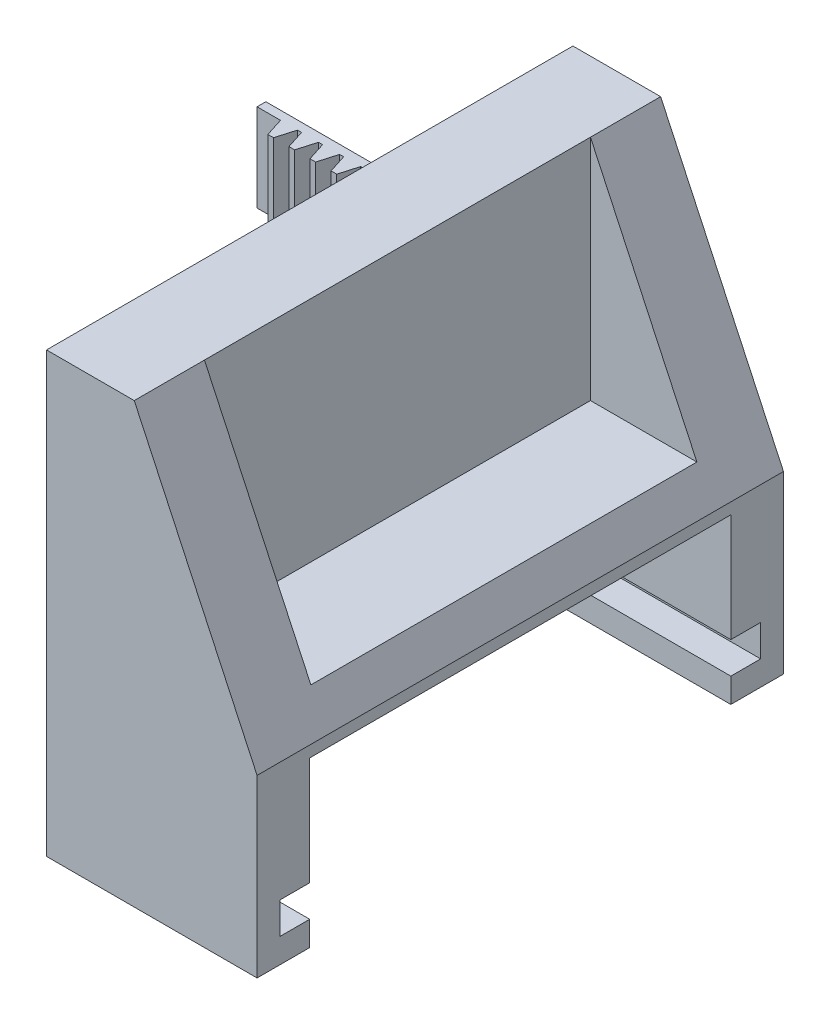
SolidWorks part; units mm, degrees
ref_plane "Front Plane" through (0, 0, 0) normal (0, 0, 1) x (1, 0, 0)
ref_plane "Top Plane" through (0, 0, 0) normal (0, 1, 0) x (1, 0, 0)
ref_plane "Right Plane" through (0, 0, 0) normal (1, 0, 0) x (0, 0, -1)
sketch "Sketch1" plane through (0, 0, 0) normal (0, 0, 1) x (1, 0, 0)
  line L0 (0, 0) -> (0, -25)
  line L1 (0, -25) -> (12, -25)
  line L2 (12, -25) -> (12, -15)
  line L3 (12, -15) -> (5, 0)
  line L4 (5, 0) -> (0, 0)
  dimension "D1" = 25
  dimension "D2" = 12
  dimension "D3" = 10
  dimension "D4" = 5
extrude "Boss-Extrude1" add sketch "Sketch1" against normal blind 30
sketch "Sketch4" plane through (0, 0, 0) normal (-1, 0, 0) x (0, 0, 1)
  line L0 (-30, 0) -> (-30, -25) construction
  line L1 (-27, -15.6386) -> (-3, -15.6386)
  line L2 (-27, -15.6386) -> (-27, -29.6386)
  line L3 (-27, -29.6386) -> (-3, -29.6386)
  line L4 (-3, -15.6386) -> (-3, -29.6386)
  point P4 (-27, -22.6386)
  dimension "D1" = 24
  dimension "D2" = 14
  dimension "D3" = 3
extrude "Cut-Extrude2" cut sketch "Sketch4" against normal blind 25 contours L2 L1 L4 L3
sketch "Sketch5" plane through (0, 0, 0) normal (-1, 0, 0) x (0, 0, 1)
  line L0 (-3, -15.6386) -> (-3, -25) construction
  line L1 (-3, -21.8) -> (-1.3, -21.8)
  line L2 (-3, -21.8) -> (-3, -23.6)
  line L3 (-3, -23.6) -> (-1.3, -23.6)
  line L4 (-1.3, -21.8) -> (-1.3, -23.6)
  line L5 (-3, -25) -> (0, -25) construction
  dimension "D1" = 1.8
  dimension "D2" = 1.7
  dimension "D3" = 1.4
extrude "Cut-Extrude3" cut sketch "Sketch5" against normal blind 15
ref_plane "Plane1" through (0, 0, -15) normal (0, 0, 1) x (1, 0, 0)
mirror "Mirror1" about plane through (0, 0, -15) normal (0, 0, 1) of "Cut-Extrude3"
sketch "Sketch6" plane through (0, 0, -15) normal (0, 0, 1) x (1, 0, 0)
  line L0 (5, 0) -> (5, -13)
  line L1 (5, -13) -> (11.0667, -13)
  line L2 (12, -15) -> (5, 0) construction
  line L3 (11.0667, -13) -> (5, 0)
  dimension "D1" = 13
extrude "Cut-Extrude4" cut sketch "Sketch6" against normal mid plane 22
ref_plane "Plane2" through (0, -15, 0) normal (0, 1, 0) x (1, 0, 0)
sketch "Sketch7" plane through (0, -15, 0) normal (0, 1, 0) x (1, 0, 0)
  line L0 (0, 28.5) -> (-16, 28.5)
  line L1 (0, 30) -> (0, 0) construction
  line L3 (0, 28.5) -> (0, 28)
  line L4 (0, 28) -> (-0.5, 28)
  line L47 (-0.5, 28) -> (-0.8043, 26.9435)
  line L62 (-6.6, 15) -> (6.6, 15) construction
  line L63 (-0.8043, 26.9435) -> (-1.1273, 26.9435)
  line L64 (-1.1273, 26.9435) -> (-1.4655, 28)
  line L65 (-2.3273, 26.9435) -> (-2.6655, 28)
  line L66 (-2.0043, 26.9435) -> (-2.3273, 26.9435)
  line L67 (-1.7, 28) -> (-2.0043, 26.9435)
  line L68 (-3.5273, 26.9435) -> (-3.8655, 28)
  line L69 (-3.2043, 26.9435) -> (-3.5273, 26.9435)
  line L70 (-2.9, 28) -> (-3.2043, 26.9435)
  line L71 (-4.7273, 26.9435) -> (-5.0655, 28)
  line L72 (-4.4043, 26.9435) -> (-4.7273, 26.9435)
  line L73 (-4.1, 28) -> (-4.4043, 26.9435)
  line L74 (-5.9273, 26.9435) -> (-6.2655, 28)
  line L75 (-5.6043, 26.9435) -> (-5.9273, 26.9435)
  line L76 (-5.3, 28) -> (-5.6043, 26.9435)
  line L77 (-7.1273, 26.9435) -> (-7.4655, 28)
  line L78 (-6.8043, 26.9435) -> (-7.1273, 26.9435)
  line L79 (-6.5, 28) -> (-6.8043, 26.9435)
  line L80 (-8.3273, 26.9435) -> (-8.6655, 28)
  line L81 (-8.0043, 26.9435) -> (-8.3273, 26.9435)
  line L82 (-7.7, 28) -> (-8.0043, 26.9435)
  line L83 (-9.5273, 26.9435) -> (-9.8655, 28)
  line L84 (-9.2043, 26.9435) -> (-9.5273, 26.9435)
  line L85 (-8.9, 28) -> (-9.2043, 26.9435)
  line L86 (-10.7273, 26.9435) -> (-11.0655, 28)
  line L87 (-10.4043, 26.9435) -> (-10.7273, 26.9435)
  line L88 (-10.1, 28) -> (-10.4043, 26.9435)
  line L89 (-11.9273, 26.9435) -> (-12.2655, 28)
  line L90 (-11.6043, 26.9435) -> (-11.9273, 26.9435)
  line L91 (-11.3, 28) -> (-11.6043, 26.9435)
  line L92 (-13.1273, 26.9435) -> (-13.4655, 28)
  line L93 (-12.8043, 26.9435) -> (-13.1273, 26.9435)
  line L94 (-12.5, 28) -> (-12.8043, 26.9435)
  line L95 (-14.3273, 26.9435) -> (-14.6655, 28)
  line L96 (-14.0043, 26.9435) -> (-14.3273, 26.9435)
  line L97 (-13.7, 28) -> (-14.0043, 26.9435)
  line L98 (-1.4655, 28) -> (-1.7, 28)
  line L99 (-2.6655, 28) -> (-2.9, 28)
  line L100 (-3.8655, 28) -> (-4.1, 28)
  line L101 (-5.0655, 28) -> (-5.3, 28)
  line L102 (-6.2655, 28) -> (-6.5, 28)
  line L103 (-7.4655, 28) -> (-7.7, 28)
  line L104 (-8.6655, 28) -> (-8.9, 28)
  line L105 (-9.8655, 28) -> (-10.1, 28)
  line L106 (-11.0655, 28) -> (-11.3, 28)
  line L107 (-14.9, 28) -> (-16, 28)
  line L108 (-16, 28) -> (-16, 28.5)
  line L109 (-12.2655, 28) -> (-12.5, 28)
  line L110 (-13.4655, 28) -> (-13.7, 28)
  line L111 (-14.6655, 28) -> (-14.9, 28)
  point P9 (0, 0)
  point P55 (0, 0)
  point P56 (0, 0)
  dimension "D1" = 12
  dimension "D2" = 16
  dimension "D3" = 0.5
  dimension "D6" = 0.5
  dimension "D7" = 13.5
extrude "Boss-Extrude2" add sketch "Sketch7" along normal blind 5
